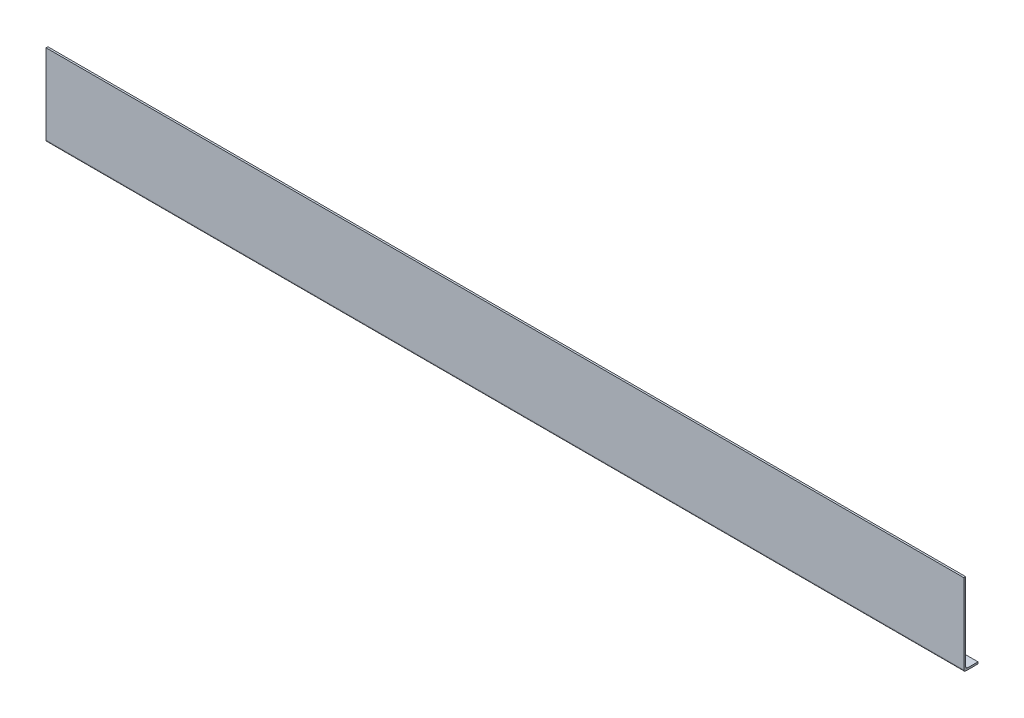
SolidWorks part; units mm, degrees
ref_plane "Front Plane" through (0, 0, 0) normal (0, 0, 1) x (1, 0, 0)
ref_plane "Top Plane" through (0, 0, 0) normal (0, 1, 0) x (1, 0, 0)
ref_plane "Right Plane" through (0, 0, 0) normal (1, 0, 0) x (0, 0, -1)
sketch "Sketch1" plane through (0, 0, 0) normal (1, 0, 0) x (0, 0, -1)
  line L0 (0, 0) -> (-23, 0)
  line L1 (-23, 0) -> (-23, 133)
  line L2 (0, 3) -> (-20, 3)
  line L3 (-20, 3) -> (-20, 133)
  line L4 (-23, 133) -> (-20, 133)
  line L5 (0, 3) -> (0, 0)
  dimension "D1" = 3
  dimension "D2" = 133
  dimension "D3" = 23
extrude "Boss-Extrude1" add sketch "Sketch1" along normal blind 1493
fillet "Fillet1" radius 3 2 edges at (746.5, 3, 20) (746.5, 0, 23)
equation "\"1Bar_Side_RB_3mm_length\"=1493.0"
equation "\"D1@Boss-Extrude1\"=\"1Bar_Side_RB_3mm_length\""
equation "\"CarBeamWidth\"=700.0"
equation "\"WheelWidth\"=650.0"
equation "\"Wheel_FrontBoxDistance\"=1390.0"
equation "\"MetalSheet_3mm_length\"=5030.0"
equation "\"MetalSheet_3mm_width\"=1923.0"
equation "\"MetalSheet_3mm_FloorCut_L_length\"=1764.0"
equation "\"MetalSheet_3mm_FloorCut_L_disdance\"=1665.0"
equation "\"MetalSheet_3mm_FloorCut_R_length\"=1764.0"
equation "\"MetalSheet_3mm_FloorCut_R_disdance\"=1665.0"
equation "\"indoorHeight\"=1940.0"
equation "\"haveDoor_R\"=1"
equation "\"1Bar_Side_RF_3mm_length\"=1493.0"
equation "\"DoorSeparator_RF_3mm_withHinge_toFrontDistance\"=1673.0"
equation "\"DoorSeparator_RF_3mm_withHinge_exist\"=1"
equation "\"DoorSeparator_RB_3mm_withHinge_toFrontDistance\"=3427.0"
equation "\"DoorSeparator_RB_3mm_withHinge_exist\"=1"
equation "\"Door_R1_L_open_Single_toFrontDistance\"=2547.5"
equation "\"Door_R1_L_open_Single_exist\"=1"
equation "\"Door_R1_R_open_Single_toFrontDistance\"=3422.0"
equation "\"Door_R1_R_open_Single_exist\"=1"
equation "\"x\"=66.0"
equation "\"da\"=62.0"
equation "\"SquareTube_length\"=1923.0"
equation "\"channelSteel_length\"=5030.0"
equation "\"SquareTube_inFront_AvgDistance\"=285.0"
equation "\"SquareTube_inFront_TotalCount\"=5"
equation "\"SquareTube_inFront1_cutDepth50_R\"=0.5"
equation "\"SquareTube_inFront1_cutDepth50_L\"=0.5"
equation "\"SquareTube_inFront2_cutDepth50_R\"=0.5"
equation "\"SquareTube_inFront2_cutDepth50_L\"=0.5"
equation "\"SquareTube_inFront3_cutDepth50_R\"=0.5"
equation "\"SquareTube_inFront3_cutDepth50_L\"=0.5"
equation "\"SquareTube_inFront4_cutDepth50_R\"=0.5"
equation "\"SquareTube_inFront4_cutDepth50_L\"=0.5"
equation "\"SquareTube_inFront5_cutDepth50_R\"=50"
equation "\"SquareTube_inFront5_cutDepth50_L\"=50"
equation "\"SquareTube_inFront6_cutDepth50_R\"=50"
equation "\"SquareTube_inFront6_cutDepth50_L\"=50"
equation "\"SquareTube_inFront7_cutDepth50_R\"=50"
equation "\"SquareTube_inFront7_cutDepth50_L\"=50"
equation "\"SquareTube_inFront8_cutDepth50_R\"=50"
equation "\"SquareTube_inFront8_cutDepth50_L\"=50"
equation "\"SquareTube_inFront9_cutDepth50_R\"=50"
equation "\"SquareTube_inFront9_cutDepth50_L\"=50"
equation "\"SquareTube_inFront10_cutDepth50_R\"=50"
equation "\"SquareTube_inFront10_cutDepth50_L\"=50"
equation "\"SquareTube_inFront11_cutDepth50_R\"=50"
equation "\"SquareTube_inFront11_cutDepth50_L\"=50"
equation "\"SquareTube_inFront12_cutDepth50_R\"=50"
equation "\"SquareTube_inFront12_cutDepth50_L\"=50"
equation "\"SquareTube_inFront13_cutDepth50_R\"=50"
equation "\"SquareTube_inFront13_cutDepth50_L\"=50"
equation "\"SquareTube_inFront14_cutDepth50_R\"=50"
equation "\"SquareTube_inFront14_cutDepth50_L\"=50"
equation "\"SquareTube_inBack_AvgDistance\"=333.125"
equation "\"SquareTube_inBack_TotalCount\"=9"
equation "\"SquareTube_inBack1_cutDepth50_R\"=50"
equation "\"SquareTube_inBack1_cutDepth50_L\"=50"
equation "\"SquareTube_inBack2_cutDepth50_R\"=50"
equation "\"SquareTube_inBack2_cutDepth50_L\"=50"
equation "\"SquareTube_inBack3_cutDepth50_R\"=50"
equation "\"SquareTube_inBack3_cutDepth50_L\"=50"
equation "\"SquareTube_inBack4_cutDepth50_R\"=50"
equation "\"SquareTube_inBack4_cutDepth50_L\"=50"
equation "\"SquareTube_inBack5_cutDepth50_R\"=50"
equation "\"SquareTube_inBack5_cutDepth50_L\"=50"
equation "\"SquareTube_inBack6_cutDepth50_R\"=0.5"
equation "\"SquareTube_inBack6_cutDepth50_L\"=0.5"
equation "\"SquareTube_inBack7_cutDepth50_R\"=0.5"
equation "\"SquareTube_inBack7_cutDepth50_L\"=0.5"
equation "\"SquareTube_inBack8_cutDepth50_R\"=0.5"
equation "\"SquareTube_inBack8_cutDepth50_L\"=0.5"
